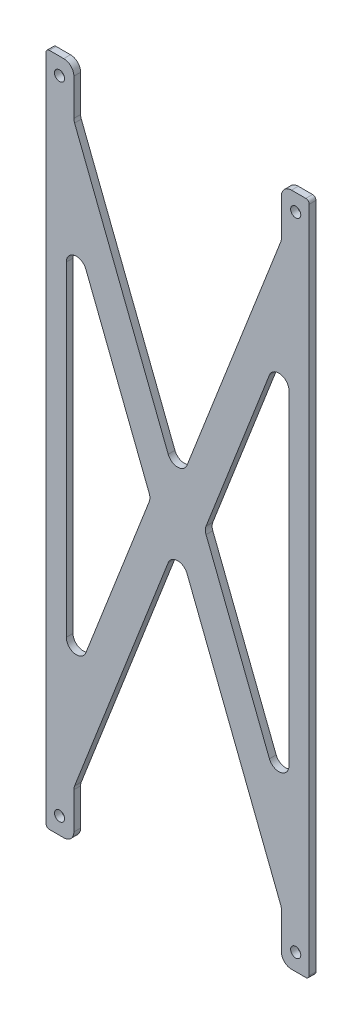
SolidWorks part; units mm, degrees
material "Hexcel AS4C (3000 丝)"
ref_plane "前视基准面" through (0, 0, 0) normal (0, 0, 1) x (1, 0, 0)
ref_plane "上视基准面" through (0, 0, 0) normal (0, 1, 0) x (1, 0, 0)
ref_plane "右视基准面" through (0, 0, 0) normal (1, 0, 0) x (0, 0, -1)
sketch "草图1" plane through (0, 0, 0) normal (0, 0, 1) x (1, 0, 0)
  line L0 (-433.5341, 0) -> (21243.1718, 0) construction
  line L1 (0, -433.5341) -> (0, 21243.1718) construction
  line L2 (-31, -100) -> (39, 79.4872)
  line L3 (-39, -100) -> (39, -100)
  line L4 (-39, -100) -> (-39, 100)
  line L5 (-39, 100) -> (39, 100)
  line L6 (39, -100) -> (39, 100)
  line L7 (-39, -100) -> (39, 100) construction
  line L8 (-39, 100) -> (39, -100) construction
  line L25 (31, -100) -> (-39, 79.4872)
  line L26 (-31, 100) -> (39, -79.4872)
  line L27 (31, 100) -> (-39, -79.4872)
  line L28 (-35, -1030.2665) -> (-35, 48969.7335) construction
  line L29 (35, -1030.2665) -> (35, 48969.7335) construction
  line L30 (33, 64.1026) -> (33, -64.1026)
  line L31 (-33, 64.1026) -> (-33, -64.1026)
  point P4 (0, 0)
  dimension "D1" = 8
  dimension "D2" = 35
  dimension "D3" = 4
  dimension "D4" = 200
  dimension "D5" = 6
extrude "凸台-拉伸1" add sketch "草图1" along normal blind 2
sketch "草图4" plane through (0, 0, 2) normal (0, 0, 1) x (1, 0, 0)
  line L0 (-39, -100) -> (-39, 100) construction
  line L1 (-39, 100) -> (-31, 100) construction
  line L2 (0, -1000) -> (0, 49000) construction
  line L4 (-754.3874, 0) -> (42673.3512, 0) construction
  circle A0 centre (-35, 95) radius 1.5
  circle A1 centre (-35, -95) radius 1.5
  circle A2 centre (35, -95) radius 1.5
  circle A3 centre (35, 95) radius 1.5
  dimension "D1" = 3
  dimension "D2" = 4
  dimension "D3" = 5
extrude "切除-拉伸3" cut sketch "草图4" against normal through all
fillet "圆角4" radius 1 8 edges at (39, -100, 1) (31, -100, 1) (-31, -100, 1) (-39, -100, 1) (31, 100, 1) (39, 100, 1) (-31, 100, 1) (-39, 100, 1)
sketch "草图6" plane through (0, 0, 2) normal (0, 0, 1) x (1, 0, 0)
  line L0 (-30.7517, -99.3633) -> (0, -20.5128) construction
  line L1 (30.7517, -99.3633) -> (0, -20.5128) construction
  line L2 (30.7517, 99.3633) -> (0, 20.5128) construction
  line L3 (-30.7517, 99.3633) -> (0, 20.5128) construction
  line L4 (-30.7517, -99.3633) -> (0, -20.5128)
  line L5 (30.7517, -99.3633) -> (0, -20.5128)
  line L6 (30.7517, 99.3633) -> (0, 20.5128)
  line L7 (-30.7517, 99.3633) -> (0, 20.5128)
  line L9 (-35.41, -97.5466) -> (0, -6.7518)
  line L10 (35.41, -97.5466) -> (0, -6.7518)
  line L11 (35.41, 97.5466) -> (0, 6.7518)
  line L12 (-35.41, 97.5466) -> (0, 6.7518)
  line L15 (-1000, 0) -> (49000, 0) construction
  line L16 (-30.7517, -99.3633) -> (-30.7517, -85.6023)
  line L17 (0, -1000) -> (0, 49000) construction
  line L18 (30.7517, -99.3633) -> (30.7517, -85.6023)
  line L19 (-30.7517, 99.3633) -> (-30.7517, 85.6023)
  line L20 (30.7517, 99.3633) -> (30.7517, 85.6023)
  dimension "D1" = 5
extrude "切除-拉伸5" cut sketch "草图6" against normal through all
fillet "圆角7" radius 3 16 edges at (30.7517, 85.6023, 1) (0, 6.7518, 1) (-30.7517, 85.6023, 1) (-30.7517, 99.3633, 1) (-30.7517, -99.3633, 1) (0, -6.7518, 1) (30.7517, -85.6023, 1) (30.7517, -99.3633, 1) (30.7517, 99.3633, 1) (33, 64.1026, 1) (33, -64.1026, 1) (8, 0, 1) (-8, 0, 1) (-33, -64.1026, 1) (-33, 64.1026, 1) (-30.7517, -85.6023, 1)
